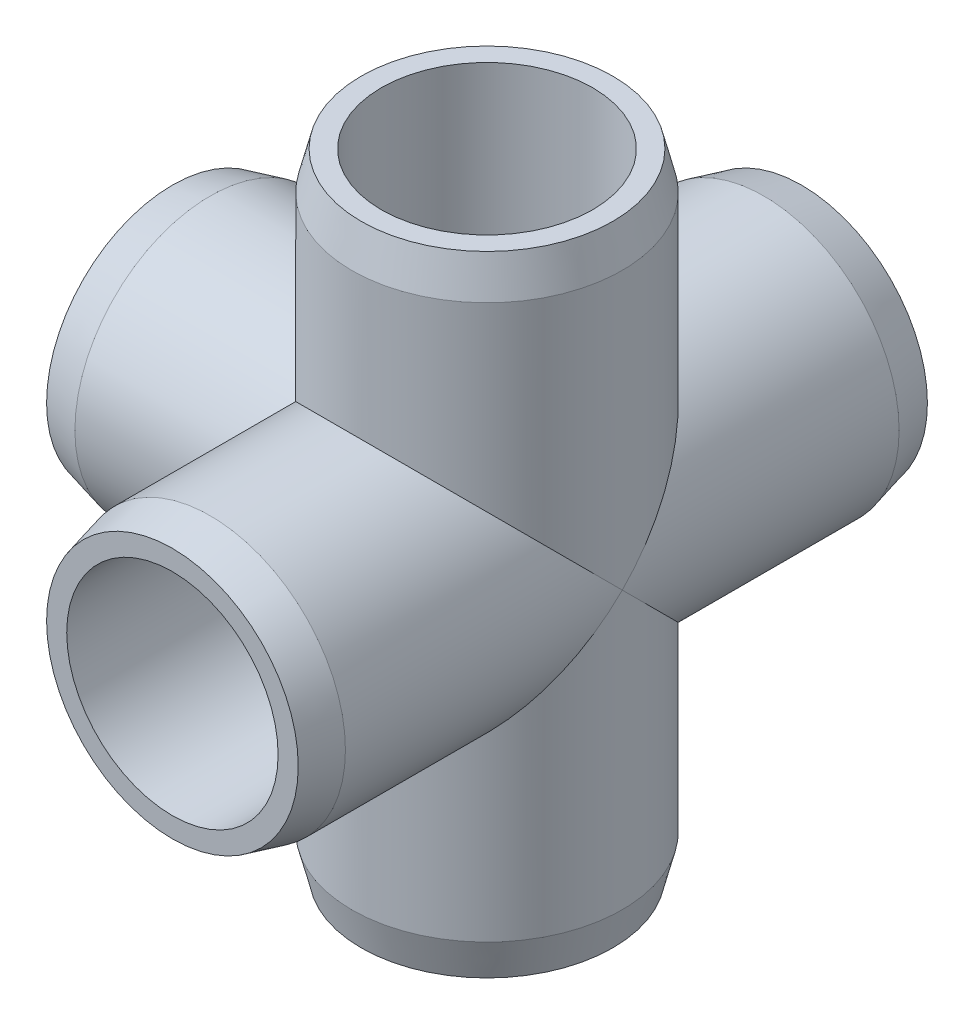
SolidWorks part; units mm, degrees
ref_plane "Front Plane" through (0, 0, 0) normal (0, 0, 1) x (1, 0, 0)
ref_plane "Top Plane" through (0, 0, 0) normal (0, 1, 0) x (1, 0, 0)
ref_plane "Right Plane" through (0, 0, 0) normal (1, 0, 0) x (0, 0, -1)
sketch "Sketch1" plane through (0, 0, 0) normal (0, 1, 0) x (1, 0, 0)
  circle A0 centre (0, 0) radius 10.668
  circle A1 centre (0, 0) radius 13.6525
  dimension "D1" = 27.305
  dimension "D2" = 21.336
extrude "Boss-Extrude1" add sketch "Sketch1" along normal blind 63.5
sketch "Sketch3" plane through (0, 0, 0) normal (0, 0, 1) x (1, 0, 0)
  line L0 (0, 0) -> (0, 63.5) construction
  circle A0 centre (0, 31.75) radius 10.668
  dimension "D2" = 21.336
  dimension "D1" = 63.5
extrude "Cut-Extrude2" cut sketch "Sketch3" against normal blind 38.1
ref_plane "Plane1" through (0, 0, -31.75) normal (0, 0, 1) x (1, 0, 0)
sketch "Sketch18" plane through (0, 0, 0) normal (0, -1, 0) x (1, 0, 0)
  circle A0 centre (0, 0) radius 10.668
sketch "Sketch4" plane through (0, 0, -31.75) normal (0, 0, 1) x (1, 0, 0)
  line L0 (0, 0) -> (0, 63.5) construction
  circle A0 centre (0, 31.75) radius 13.6525
  circle A1 centre (0, 31.75) radius 10.668
  dimension "D2" = 27.305
  dimension "D3" = 21.336
  dimension "D1" = 63.5
  dimension "D4" = 31.75
extrude "Boss-Extrude2" add sketch "Sketch4" along normal blind 63.5
sketch "Sketch5" plane through (0, 0, 0) normal (1, 0, 0) x (0, 0, -1)
  line L0 (0, 0) -> (0, 63.5) construction
  circle A1 centre (0, 31.75) radius 10.668
  dimension "D2" = 21.336
  dimension "D1" = 63.5
extrude "Cut-Extrude3" cut sketch "Sketch5" against normal blind 69.85
ref_plane "Plane2" through (-31.75, 0, 0) normal (1, 0, 0) x (0, 0, -1)
sketch "Sketch6" plane through (-31.75, 0, 0) normal (1, 0, 0) x (0, 0, -1)
  line L0 (0, 0) -> (0, 63.5) construction
  circle A0 centre (0, 31.75) radius 13.6525
  circle A1 centre (0, 31.75) radius 10.668
  dimension "D2" = 27.305
  dimension "D3" = 21.336
  dimension "D1" = 63.5
extrude "Boss-Extrude3" add sketch "Sketch6" along normal up to surface (31.75 mm away) up to face at (0, 63.5, 13.6525)
sketch "Sketch8" plane through (0, 0, 0) normal (0, 0, 1) x (1, 0, 0)
  circle A0 centre (0, 31.75) radius 10.668
  dimension "D1" = 21.336
extrude "Cut-Extrude5" cut sketch "Sketch8" against normal blind 69.85 and the other way blind 304.8
sketch "Sketch10" plane through (0, 0, 0) normal (0, 0, 1) x (1, 0, 0)
  line L0 (10.668, 63.5) -> (-10.668, 63.5) construction
  line L1 (10.668, 63.5) -> (-10.668, 63.5) construction
  line L2 (-10.4775, 44.45) -> (-9.2075, 44.45)
  line L3 (-9.2075, 44.45) -> (-9.2075, 42.545)
  line L4 (-9.2075, 42.545) -> (-10.4775, 42.545)
  line L5 (-10.4775, 42.545) -> (-10.4775, 44.45)
  line L6 (0, 63.5) -> (0, 11.6293) construction
  dimension "D1" = 19.05
  dimension "D2" = 1.27
  dimension "D3" = 1.905
sketch "Sketch11" plane through (0, 0, 0) normal (0, 0, 1) x (1, 0, 0)
  line L0 (-10.668, 0) -> (10.668, 0) construction
  line L1 (-10.668, 0) -> (10.668, 0) construction
  line L2 (-10.4775, 19.05) -> (-9.2075, 19.05)
  line L3 (-9.2075, 19.05) -> (-9.2075, 20.955)
  line L4 (-9.2075, 20.955) -> (-10.4775, 20.955)
  line L5 (-10.4775, 20.955) -> (-10.4775, 19.05)
  line L6 (0, 0) -> (0, 49.8766) construction
  dimension "D1" = 1.905
  dimension "D2" = 1.27
  dimension "D3" = 19.05
  dimension "D4" = 3.175
sketch "Sketch12" plane through (0, 0, 0) normal (0, 0, 1) x (1, 0, 0)
  line L0 (-31.75, 42.418) -> (-31.75, 21.082) construction
  line L1 (-31.75, 42.418) -> (-31.75, 21.082) construction
  line L2 (-10.795, 42.2275) -> (-10.795, 40.9575)
  line L3 (-10.795, 40.9575) -> (-12.7, 40.9575)
  line L4 (-12.7, 40.9575) -> (-12.7, 42.2275)
  line L5 (-12.7, 42.2275) -> (-10.795, 42.2275)
  line L6 (-31.75, 31.75) -> (3.4291, 31.75) construction
  dimension "D1" = 1.905
  dimension "D2" = 1.27
  dimension "D3" = 3.175
  dimension "D4" = 19.05
ref_plane "Plane3" through (0, 0, -4.445) normal (0, 0, -1) x (-1, 0, 0)
revolve "Revolve5" add sketch "Sketch11" angle 360 about L6
revolve "Revolve6" add sketch "Sketch12" angle 360 about L6
sketch "Sketch13" plane through (0, 0, 0) normal (1, 0, 0) x (0, 0, -1)
  line L0 (31.75, 42.418) -> (12.7, 42.418) construction
  line L1 (0, 42.418) -> (-31.75, 42.418) construction
  line L2 (12.7, 42.418) -> (12.7, 41.148)
  line L3 (12.7, 41.148) -> (10.795, 41.148)
  line L4 (10.795, 41.148) -> (10.795, 42.418)
  line L5 (10.795, 42.418) -> (12.7, 42.418)
  line L6 (31.75, 21.082) -> (31.75, 42.418) construction
  line L7 (31.75, 21.082) -> (31.75, 42.418) construction
  line L8 (31.75, 31.75) -> (-5.1648, 31.75) construction
  dimension "D1" = 19.05
  dimension "D2" = 1.905
  dimension "D3" = 1.27
revolve "Revolve7" add sketch "Sketch13" angle 360 about L8
sketch "Sketch14" plane through (0, 0, 0) normal (1, 0, 0) x (0, 0, -1)
  line L0 (-13.6525, 0) -> (13.6525, 0) construction
  line L1 (-13.6525, 0) -> (13.6525, 0) construction
  line L2 (13.6525, 0) -> (13.6525, 3.81)
  line L4 (0, 0) -> (12.7, 0) construction
  line L5 (12.7, 0) -> (13.6525, 0)
  line L6 (13.6525, 0) -> (13.7035, 0.1387)
  line L7 (12.7, 0) -> (13.6525, 3.81)
  line L8 (0, 0) -> (0, 19.4643) construction
  dimension "D1" = 3.81
  dimension "D2" = 0.9525
revolve "Cut-Revolve1" cut sketch "Sketch14" angle 360 about L8
ref_plane "Plane4" through (0, 31.75, 0) normal (0, 1, 0) x (1, 0, 0)
mirror "Mirror1" about plane through (0, 31.75, 0) normal (0, 1, 0) of "Cut-Revolve1"
sketch "Sketch15" plane through (0, 31.75, 0) normal (0, 1, 0) x (1, 0, 0)
  line L0 (13.6525, 31.75) -> (-13.6525, 31.75) construction
  line L1 (13.6525, 31.75) -> (-13.6525, 31.75) construction
  line L2 (-13.6525, 31.75) -> (-13.6525, 27.94)
  line L3 (-13.6525, 31.75) -> (-13.6525, 13.6525) construction
  line L4 (-13.6525, 31.75) -> (-12.7, 31.75)
  line L5 (-13.6525, 27.94) -> (-12.7, 31.75)
  line L6 (0, 31.75) -> (0, 28.8121) construction
  dimension "D1" = 3.81
  dimension "D2" = 0.9525
revolve "Cut-Revolve2" cut sketch "Sketch15" angle 360 about L6
sketch "Sketch16" plane through (0, 31.75, 0) normal (0, 1, 0) x (1, 0, 0)
  line L0 (-31.75, 13.6525) -> (-31.75, -13.6525) construction
  line L1 (-31.75, 13.6525) -> (-31.75, -13.6525) construction
  line L2 (-31.75, -13.6525) -> (-27.94, -13.6525)
  line L3 (-31.75, -13.6525) -> (-13.6525, -13.6525) construction
  line L4 (-31.75, -13.6525) -> (-31.75, -12.7)
  line L5 (-27.94, -13.6525) -> (-31.75, -12.7)
  line L6 (-31.75, 0) -> (-29.6083, 0) construction
  dimension "D1" = 3.81
  dimension "D2" = 0.9525
revolve "Cut-Revolve3" cut sketch "Sketch16" angle 360 about L6
extrude "Cut-Extrude6" cut sketch "Sketch18" against normal blind 63.5
mirror "Mirror2" about plane through (0, 0, 0) normal (0, 0, 1) of "Cut-Revolve2"
ref_plane "Plane5" through (0, 0, 0) normal (0, 0, -1) x (-1, 0, 0)
mirror "Mirror3" about plane through (0, 0, 0) normal (0, 0, -1) of "Revolve7"
sketch "Sketch19" plane through (0, 0, 0) normal (1, 0, 0) x (0, 0, -1)
  line L0 (-10.668, 0) -> (10.668, 0) construction
  line L1 (-10.668, 0) -> (10.668, 0) construction
  line L2 (-10.668, 20.955) -> (-9.398, 20.955)
  line L3 (-10.668, 21.082) -> (-10.668, 0) construction
  line L4 (-9.398, 20.955) -> (-9.398, 19.05)
  line L5 (-9.398, 19.05) -> (-10.668, 19.05)
  line L6 (-10.668, 21.082) -> (-10.668, 0) construction
  line L7 (-10.668, 19.05) -> (-10.668, 20.955)
  line L8 (0, 0) -> (0, 29.1674) construction
  dimension "D1" = 19.05
  dimension "D2" = 1.27
  dimension "D3" = 1.905
revolve "Revolve8" add sketch "Sketch19" angle 360 about L8
ref_plane "Plane6" through (0, 31.75, 0) normal (0, 1, 0) x (1, 0, 0)
mirror "Mirror4" about plane through (0, 31.75, 0) normal (0, 1, 0) of "Revolve8"
